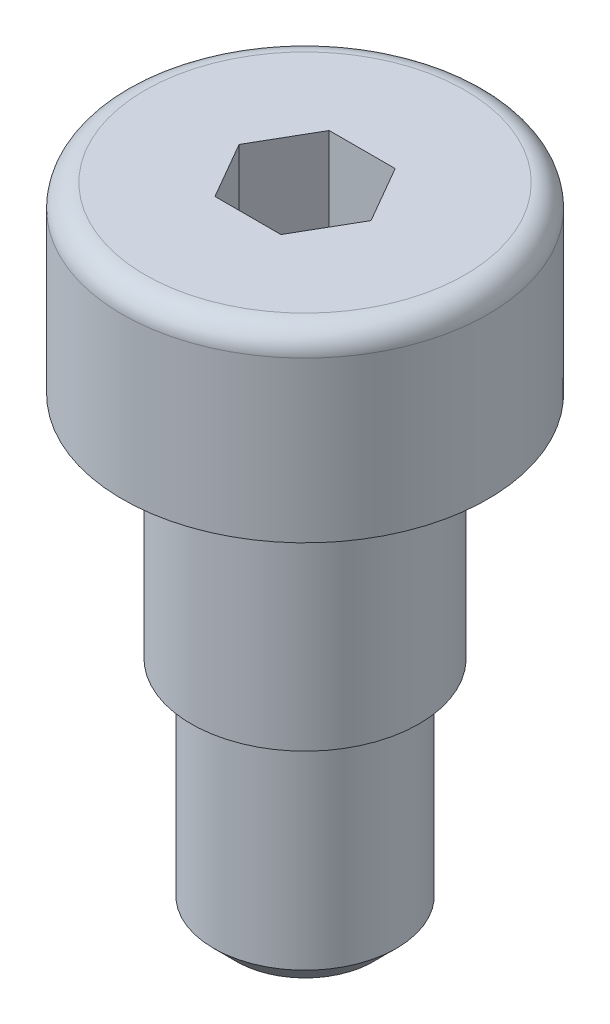
SolidWorks part; units mm, degrees
material "1023 Tôle d'acier au carbone (SS)"
ref_plane "Plan de face" through (0, 0, 0) normal (0, 0, 1) x (1, 0, 0)
ref_plane "Plan de dessus" through (0, 0, 0) normal (0, 1, 0) x (1, 0, 0)
ref_plane "Plan de droite" through (0, 0, 0) normal (1, 0, 0) x (0, 0, -1)
sketch "Esquisse1" plane through (0, 0, 0) normal (0, 0, 1) x (1, 0, 0)
  line L0 (0, 15.8257) -> (0, -15.8257) construction
  line L1 (0, 4) -> (-3.5, 4)
  line L2 (-4, 3.5) -> (-4, 0)
  line L3 (-4, 0) -> (-2.4935, 0)
  line L4 (-2, -5.013) -> (-2, -9.513)
  line L5 (-2, -9.513) -> (-1.5, -10.013)
  line L6 (-1.5, -10.013) -> (0, -10.013)
  line L7 (0, 4) -> (0, -10.013)
  line L8 (-2.4935, 0) -> (-2.4935, -5.013)
  line L9 (-2.4935, -5.013) -> (-2, -5.013)
  arc A0 (-3.5, 4) -> (-4, 3.5) centre (-3.5, 3.5) ccw
  point P11 (-2, -10.013)
  dimension "D5" = 0.5
  dimension "D1" = 8
  dimension "D2" = 4.987
  dimension "D3" = 5
  dimension "D4" = 4
  dimension "D8" = 0.5
  dimension "D6" = 4
  dimension "D7" = 5.013
revolve "Révolution1" add sketch "Esquisse1" angle 360 about L0
cosmetic thread "Représentation de filetage1" parameters "D2"=3.2
sketch "Esquisse2" plane through (0, 4, 0) normal (0, 1, 0) x (-1, 0, 0)
  line L1 (-1.4434, 0) -> (-0.7217, -1.25)
  line L2 (-0.7217, -1.25) -> (0.7217, -1.25)
  line L3 (0.7217, -1.25) -> (1.4434, 0)
  line L4 (1.4434, 0) -> (0.7217, 1.25)
  line L5 (0.7217, 1.25) -> (-0.7217, 1.25)
  line L6 (-0.7217, 1.25) -> (-1.4434, 0)
  circle A0 centre (0, 0) radius 1.25 construction
  dimension "D1" = 2.5
extrude "Enlèv. mat.-Extru.1" cut sketch "Esquisse2" against normal blind 2
